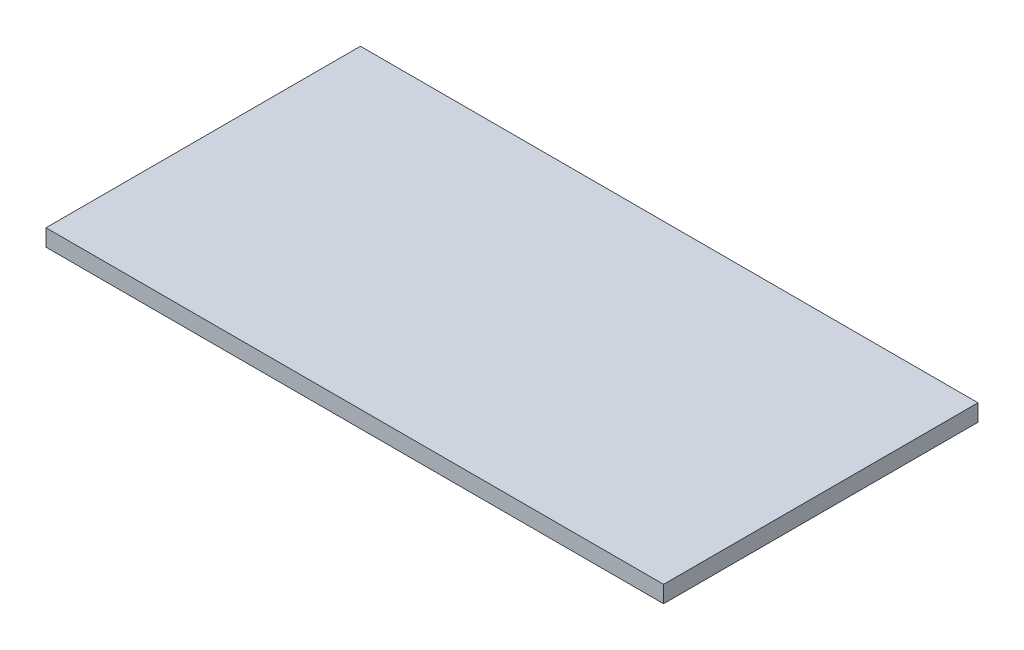
SolidWorks part; units mm, degrees
ref_plane "Front Plane" through (0, 0, 0) normal (0, 0, 1) x (1, 0, 0)
ref_plane "Top Plane" through (0, 0, 0) normal (0, 1, 0) x (1, 0, 0)
ref_plane "Right Plane" through (0, 0, 0) normal (1, 0, 0) x (0, 0, -1)
sketch "Sketch1" plane through (0, 0, 0) normal (0, 1, 0) x (1, 0, 0)
  line L1 (-90.0205, 49.9081) -> (129.9795, 49.9081)
  line L2 (-90.0205, 49.9081) -> (-90.0205, -62.0919)
  line L3 (-90.0205, -62.0919) -> (129.9795, -62.0919)
  line L4 (129.9795, 49.9081) -> (129.9795, -62.0919)
  dimension "D1" = 112
  dimension "D2" = 220
extrude "Boss-Extrude1" add sketch "Sketch1" along normal blind 6
